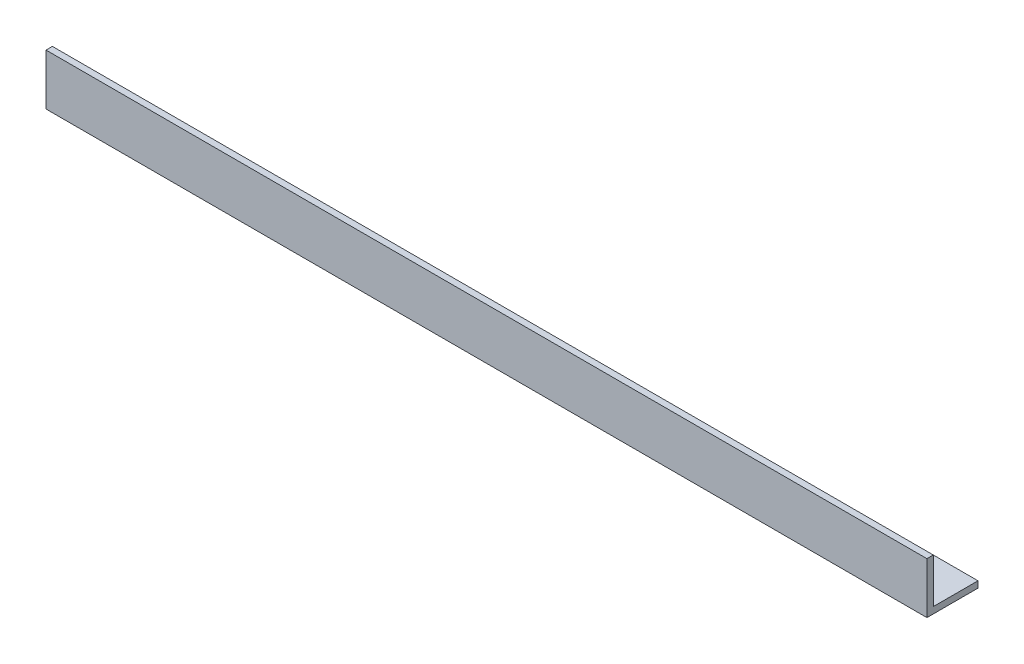
SolidWorks part; units mm, degrees
ref_plane "Front" through (0, 0, 0) normal (0, 0, 1) x (1, 0, 0)
ref_plane "Top" through (0, 0, 0) normal (0, 1, 0) x (1, 0, 0)
ref_plane "Right" through (0, 0, 0) normal (1, 0, 0) x (0, 0, -1)
sketch "Sketch2" plane through (0, 0, 0) normal (1, 0, 0) x (0, 0, -1)
  line L0 (0, 0) -> (0, 12.7)
  line L1 (0, 12.7) -> (1.5875, 12.7)
  line L2 (1.5875, 12.7) -> (1.5875, 1.5875)
  line L3 (1.5875, 1.5875) -> (12.7, 1.5875)
  line L4 (12.7, 1.5875) -> (12.7, 0)
  line L5 (12.7, 0) -> (0, 0)
  dimension "D1" = 12.7
  dimension "D2" = 1.5875
extrude "Boss-Extrude1" add sketch "Sketch2" along normal blind 219.075
